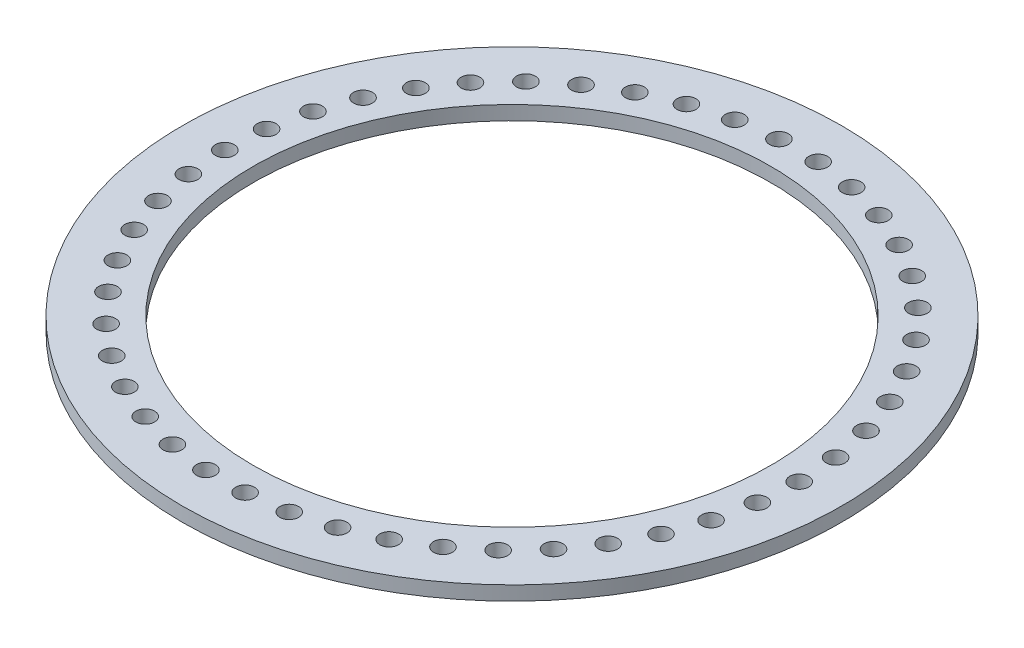
SolidWorks part; units mm, degrees
ref_plane "Front Plane" through (0, 0, 0) normal (0, 0, 1) x (1, 0, 0)
ref_plane "Top Plane" through (0, 0, 0) normal (0, 1, 0) x (1, 0, 0)
ref_plane "Right Plane" through (0, 0, 0) normal (1, 0, 0) x (0, 0, -1)
sketch "Sketch1" plane through (0, 0, 0) normal (0, 1, 0) x (1, 0, 0)
  circle A0 centre (0, 0) radius 35
  circle A1 centre (0, 0) radius 27.5
  dimension "D1" = 55
  dimension "D2" = 70
extrude "Boss-Extrude1" add sketch "Sketch1" along normal blind 1.5
sketch "Sketch2" plane through (0, 1.5, 0) normal (0, 1, 0) x (1, 0, 0)
  line L0 (0, 0) -> (36.0161, 0) construction
  circle A0 centre (30.5, 0) radius 1
  dimension "D1" = 2
  dimension "D2" = 30.5
extrude "Cut-Extrude1" cut sketch "Sketch2" against normal blind 1.5
pattern_circular "CirPattern1" count 46 over 360 about axis through (0, 0, 0) along (0, 1, 0) of "Cut-Extrude1"
